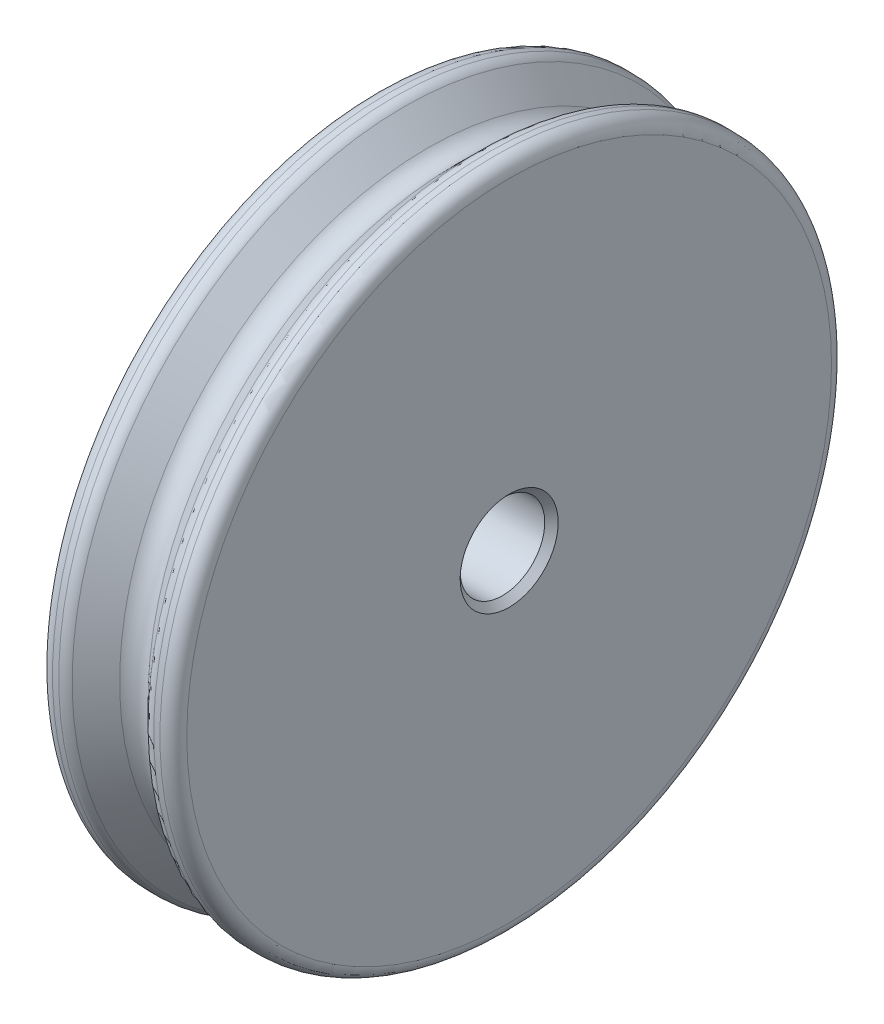
SolidWorks part; units mm, degrees
material "PE faible/moyenne densité"
ref_plane "Plan de face" through (0, 0, 0) normal (0, 0, 1) x (1, 0, 0)
ref_plane "Plan de dessus" through (0, 0, 0) normal (0, 1, 0) x (1, 0, 0)
ref_plane "Plan de droite" through (0, 0, 0) normal (1, 0, 0) x (0, 0, -1)
sketch "Esquisse2" plane through (0, 0, 0) normal (0, 0, 1) x (1, 0, 0)
  line L0 (0, 20.5) -> (0, -44.0837) construction
  line L1 (0, -55) -> (0, 55) construction
  line L2 (-80.8385, 0) -> (85.0582, 0) construction
  line L3 (55, 0) -> (-55, 0) construction
  line L4 (3.1213, 25) -> (5, 25)
  line L5 (-5, 3.15) -> (5, 3.15)
  line L6 (-5, 3.15) -> (-5, 25)
  line L7 (-5, 25) -> (-3.1213, 25)
  line L8 (5, 3.15) -> (5, 25)
  line L9 (-5, 3.15) -> (5, 25) construction
  line L10 (-5, 25) -> (5, 3.15) construction
  line L11 (-3.1213, 25) -> (-1.0607, 22.9393)
  line L12 (1.0607, 22.9393) -> (3.1213, 25)
  arc A1 (-1.0607, 22.9393) -> (1.0607, 22.9393) centre (0, 24) ccw
  point P9 (0, 14.075)
  point P20 (0, 21.8787)
  dimension "D4" = 1.5
  dimension "D5" = 45
  dimension "D1" = 10
  dimension "D2" = 6.3
  dimension "D3" = 50
revolve "Révolution1" add sketch "Esquisse2" angle 360 about L2
chamfer "Chanfrein1" distance 0.5 angle 45 2 edges at (-5, -3.15, 0) (5, -3.15, 0)
fillet "Congé1" radius 1 4 edges at (5, -25, 0) (-5, -25, 0) (3.1213, -25, 0) (-3.1213, -25, 0)
